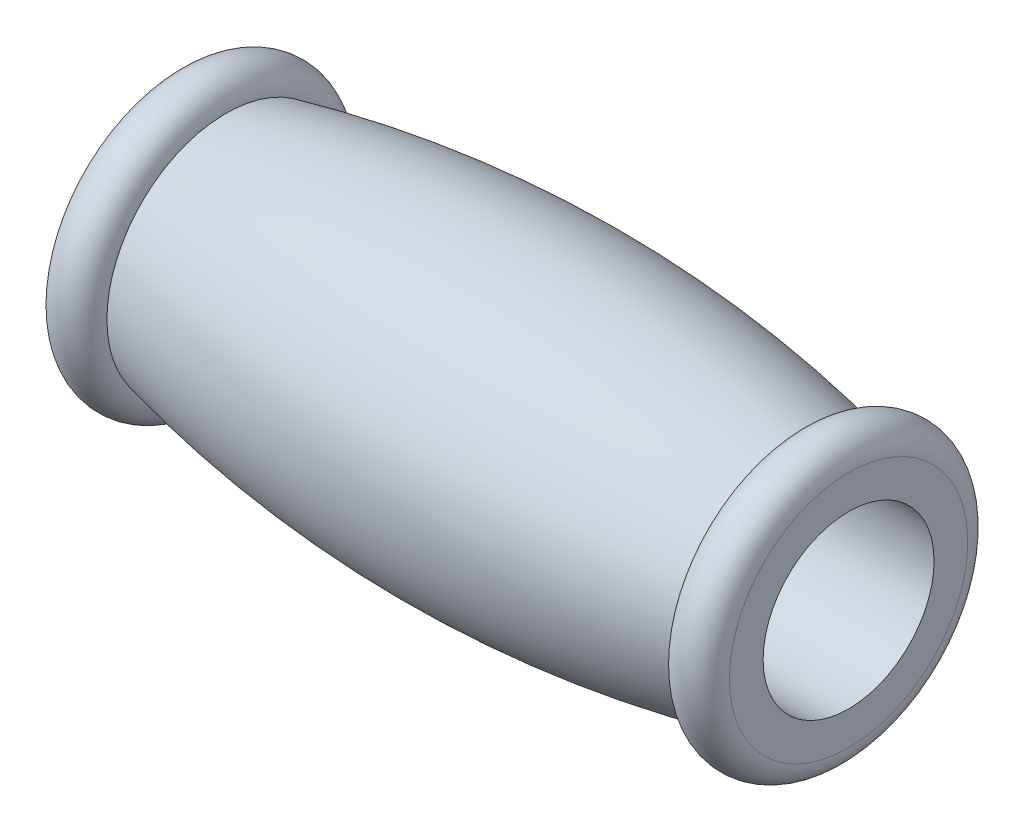
SolidWorks part; units mm, degrees
ref_plane "Front Plane" through (0, 0, 0) normal (0, 0, 1) x (1, 0, 0)
ref_plane "Top Plane" through (0, 0, 0) normal (0, 1, 0) x (1, 0, 0)
ref_plane "Right Plane" through (0, 0, 0) normal (1, 0, 0) x (0, 0, -1)
sketch "Sketch1" plane through (0, 0, 0) normal (0, 0, 1) x (1, 0, 0)
  line L0 (-100, 0) -> (119.2913, 0) construction
  line L1 (-50, 12.7) -> (50, 12.7)
  line L2 (0, 0) -> (0, 12.7) construction
  line L4 (-50, 12.7) -> (-50, 17.7)
  line L7 (50, 12.7) -> (50, 17.7)
  arc A0 (-42.5, 17.7) -> (-50, 17.7) centre (-46.25, 17.7) ccw
  arc A1 (-42.5, 17.7) -> (42.5, 17.7) centre (0, -166.8943) cw
  arc A2 (50, 17.7) -> (42.5, 17.7) centre (46.25, 17.7) ccw
  point P5 (0, 12.7)
  point P11 (0, 17.7)
  dimension "D1" = 100
  dimension "D2" = 85
  dimension "D4" = 12.7
revolve "Revolve1" add sketch "Sketch1" angle 360 about L0
